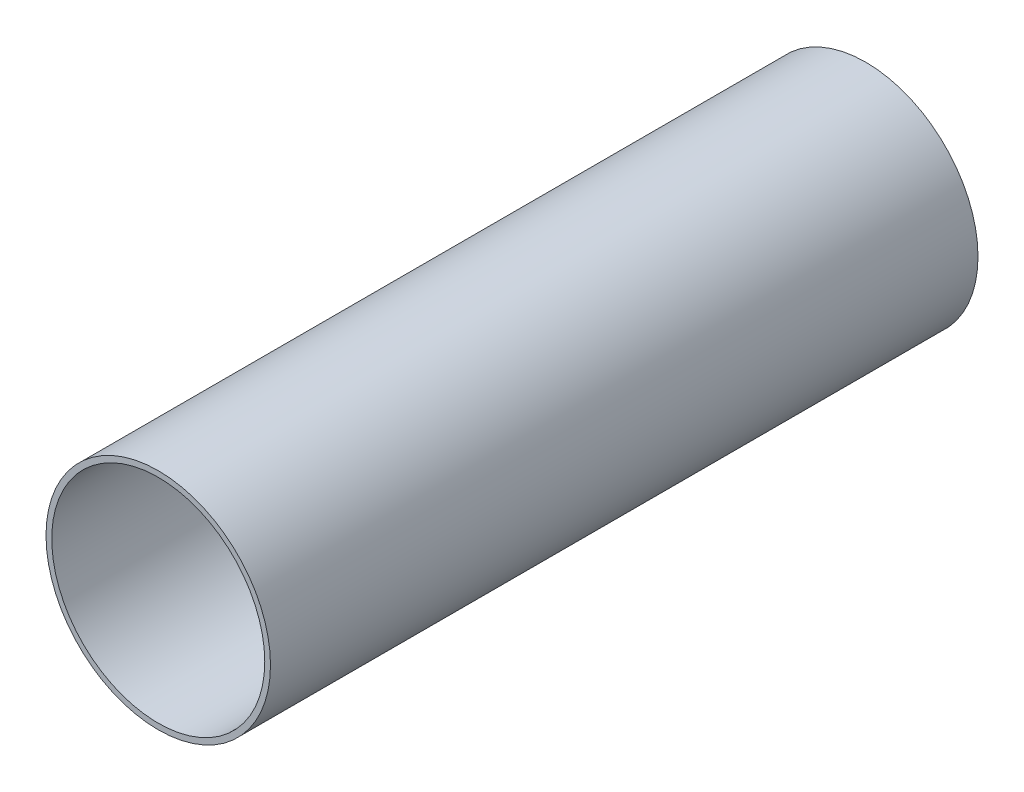
SolidWorks part; units mm, degrees
material "Copper"
ref_plane "Front Plane" through (0, 0, 0) normal (0, 0, 1) x (1, 0, 0)
ref_plane "Top Plane" through (0, 0, 0) normal (0, 1, 0) x (1, 0, 0)
ref_plane "Right Plane" through (0, 0, 0) normal (1, 0, 0) x (0, 0, -1)
sketch "Sketch1" plane through (0, 0, 0) normal (0, 0, 1) x (1, 0, 0)
  circle A0 centre (0, 0) radius 27.85
  circle A1 centre (0, 0) radius 29.35
  dimension "D1" = 55.7
  dimension "D2" = 58.7
extrude "Boss-Extrude1" add sketch "Sketch1" along normal blind 185
equation "\"Dt\"= 0.04770700"
equation "\"tag\"= 0.0048535m"
equation "\"wall thick\"= 0.0015m"
